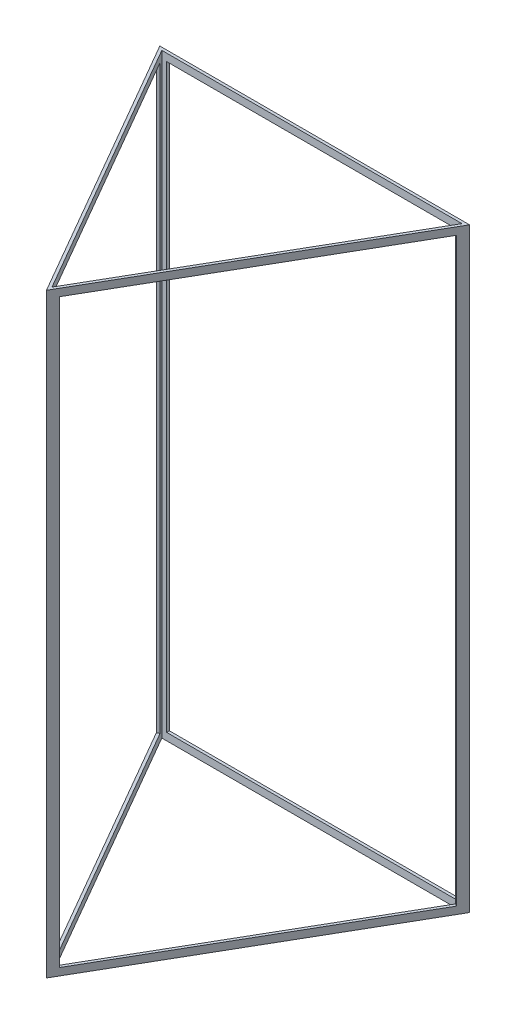
SolidWorks part; units mm, degrees
ref_plane "Front Plane" through (0, 0, 0) normal (0, 0, 1) x (1, 0, 0)
ref_plane "Top Plane" through (0, 0, 0) normal (0, 1, 0) x (1, 0, 0)
ref_plane "Right Plane" through (0, 0, 0) normal (1, 0, 0) x (0, 0, -1)
sketch "Sketch1" plane through (0, 0, 0) normal (0, 1, 0) x (1, 0, 0)
  line L6 (0, 0) -> (650, 1125.833)
  line L7 (650, 1125.833) -> (-650, 1125.833)
  line L8 (-650, 1125.833) -> (0, 0)
  line L9 (0, 23.094) -> (630, 1114.286)
  line L10 (630, 1114.286) -> (-630, 1114.286)
  line L11 (-630, 1114.286) -> (0, 23.094)
  line L12 (325, 562.9165) -> (315, 568.69) construction
  line L13 (0, 1125.833) -> (0, 1114.286) construction
  line L14 (-315, 568.69) -> (-325, 562.9165) construction
  dimension "D1" = 1300
  dimension "D2" = 1260
extrude "Boss-Extrude2" add sketch "Sketch1" along normal blind 2500
sketch "Sketch4" plane through (0, 0, -1125.833) normal (0, 0, -1) x (-1, 0, 0)
  line L0 (0, 0) -> (0, 2500) construction
  line L1 (-650, 2500) -> (650, 2500) construction
  line L3 (-609.6, 30.8) -> (609.6, 30.8)
  line L4 (-609.6, 30.8) -> (-609.6, 2469.2)
  line L5 (-609.6, 2469.2) -> (609.6, 2469.2)
  line L6 (609.6, 30.8) -> (609.6, 2469.2)
  line L7 (-609.6, 30.8) -> (609.6, 2469.2) construction
  line L8 (-609.6, 2469.2) -> (609.6, 30.8) construction
  point P5 (0, 1250)
  dimension "D1" = 1219.2
  dimension "D2" = 2438.4
extrude "Cut-Extrude2" cut sketch "Sketch4" against normal blind 21
sketch "Sketch5" plane through (0, 0, 0) normal (-0.866, 0, 0.5) x (0.5, 0, 0.866)
  line L0 (-650, 2500) -> (-650, 0) construction
  line L1 (-1300, 2500) -> (0, 2500) construction
  line L2 (-1300, 0) -> (0, 0) construction
  line L4 (-1259.6, 30.8) -> (-40.4, 30.8)
  line L5 (-1259.6, 30.8) -> (-1259.6, 2469.2)
  line L6 (-1259.6, 2469.2) -> (-40.4, 2469.2)
  line L7 (-40.4, 30.8) -> (-40.4, 2469.2)
  line L8 (-1259.6, 30.8) -> (-40.4, 2469.2) construction
  line L9 (-1259.6, 2469.2) -> (-40.4, 30.8) construction
  point P6 (-650, 1250)
  dimension "D1" = 1219.2
  dimension "D2" = 2438.4
extrude "Cut-Extrude3" cut sketch "Sketch5" against normal blind 21
sketch "Sketch6" plane through (0, 0, 0) normal (0.866, 0, 0.5) x (0.5, 0, -0.866)
  line L0 (650, 2500) -> (650, 0) construction
  line L1 (0, 2500) -> (1300, 2500) construction
  line L2 (0, 0) -> (1300, 0) construction
  line L4 (40.4, 30.8) -> (1259.6, 30.8)
  line L5 (40.4, 30.8) -> (40.4, 2469.2)
  line L6 (40.4, 2469.2) -> (1259.6, 2469.2)
  line L7 (1259.6, 30.8) -> (1259.6, 2469.2)
  line L8 (40.4, 30.8) -> (1259.6, 2469.2) construction
  line L9 (40.4, 2469.2) -> (1259.6, 30.8) construction
  point P6 (650, 1250)
  dimension "D1" = 1219.2
  dimension "D2" = 2438.4
extrude "Cut-Extrude4" cut sketch "Sketch6" against normal blind 21
